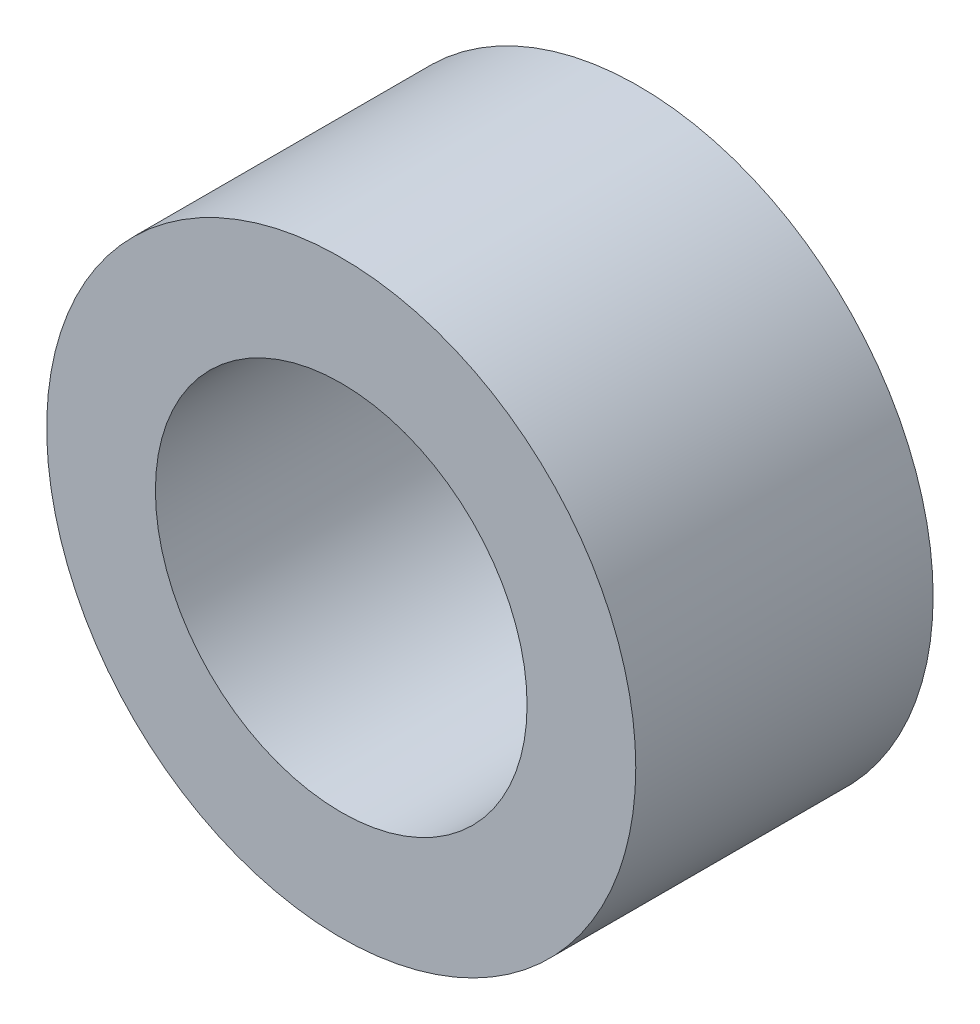
SolidWorks part; units mm, degrees
ref_plane "Front Plane" through (0, 0, 0) normal (0, 0, 1) x (1, 0, 0)
ref_plane "Top Plane" through (0, 0, 0) normal (0, 1, 0) x (1, 0, 0)
ref_plane "Right Plane" through (0, 0, 0) normal (1, 0, 0) x (0, 0, -1)
sketch "Sketch1" plane through (0, 0, 0) normal (0, 0, 1) x (1, 0, 0)
  circle A0 centre (0, 0) radius 2.5
  circle A1 centre (0, 0) radius 3.9624
  dimension "D1" = 7.9248
  dimension "D2" = 5
extrude "Boss-Extrude1" add sketch "Sketch1" along normal blind 4
